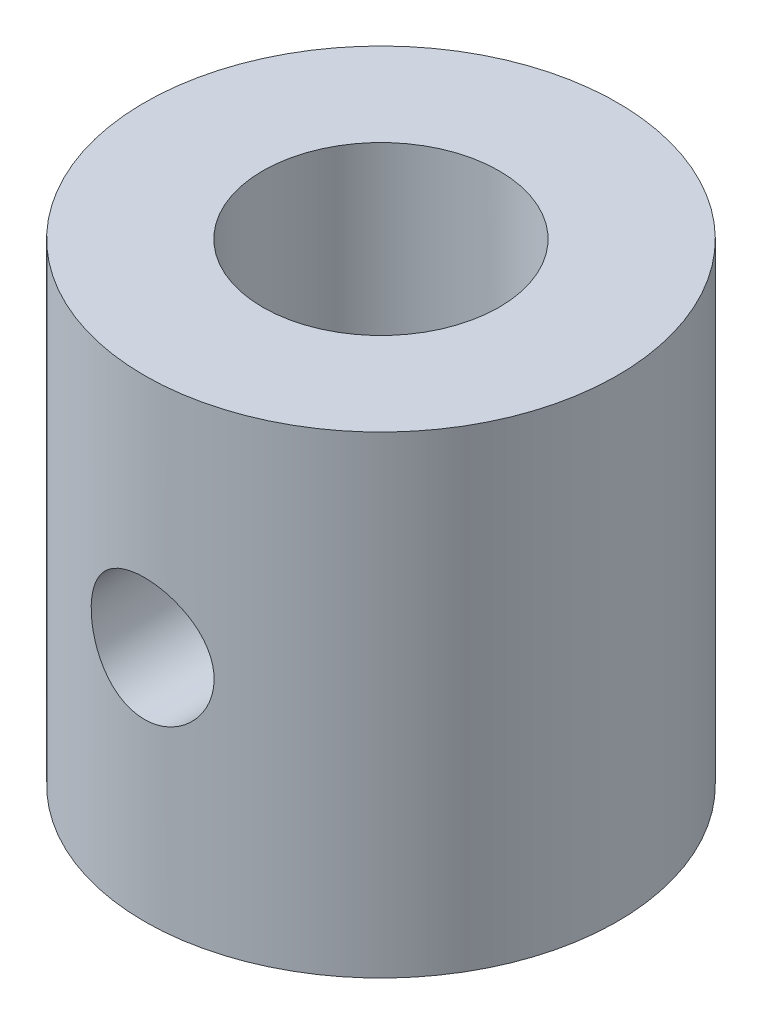
SolidWorks part; units mm, degrees
material "Stainless Steel (ferritic)"
ref_plane "Front Plane" through (0, 0, 0) normal (0, 0, 1) x (1, 0, 0)
ref_plane "Top Plane" through (0, 0, 0) normal (0, 1, 0) x (1, 0, 0)
ref_plane "Right Plane" through (0, 0, 0) normal (1, 0, 0) x (0, 0, -1)
sketch "Sketch1" plane through (0, 0, 0) normal (0, 1, 0) x (1, 0, 0)
  circle A0 centre (0, 0) radius 5
  circle A1 centre (0, 0) radius 2.5
  dimension "D1" = 10
  dimension "D2" = 5
extrude "Boss-Extrude1" add sketch "Sketch1" along normal blind 10
ref_plane "Plane1" through (0, 0, 5) normal (0, 0, 1) x (1, 0, 0)
sketch "Sketch2" plane through (0, 0, 0) normal (0, 0, 1) x (1, 0, 0)
  line L0 (-5, 10) -> (5, 10)
  line L1 (5, 10) -> (5, 0)
  line L2 (5, 0) -> (-5, 0)
  line L3 (-5, 0) -> (-5, 10)
  line L4 (0, 0) -> (0, 5) construction
  line L5 (0, 5) -> (5, 5) construction
  point P6 (5, 5)
sketch "Sketch5" plane through (0, 0, 5) normal (0, 0, 1) x (1, 0, 0)
  point P0 (0, 5)
  point P1 (-8.3433, 5.7357)
hole_wizard "M2 Clearance Hole1" positions "Sketch8" profile "Sketch9" hole size "M2" standard "ISO" end condition through all
sketch "Sketch8" plane through (0, 0, 5) normal (0, 0, 1) x (1, 0, 0)
  point P0 (0, 5)
sketch "Sketch9" plane through (0, 5, 5) normal (1, 0, 0) x (0, -1, 0)
  line L0 (0, 0) -> (0, 10)
  line L1 (0, 10) -> (1.3, 10)
  line L2 (1.3, 10) -> (1.3, 0)
  line L5 (1.3, 0) -> (0, 0)
  line L11 (0, -6.35) -> (0, 107.95) construction
  dimension "Thru Hole Dia." = 2.6
  dimension "Thru Hole Depth" = 10
other "Bounding Box"
ref_plane "Default Plane" through (-6.4086, 0, -2.9884) normal (0, 1, 0) x (1, 0, 0)
